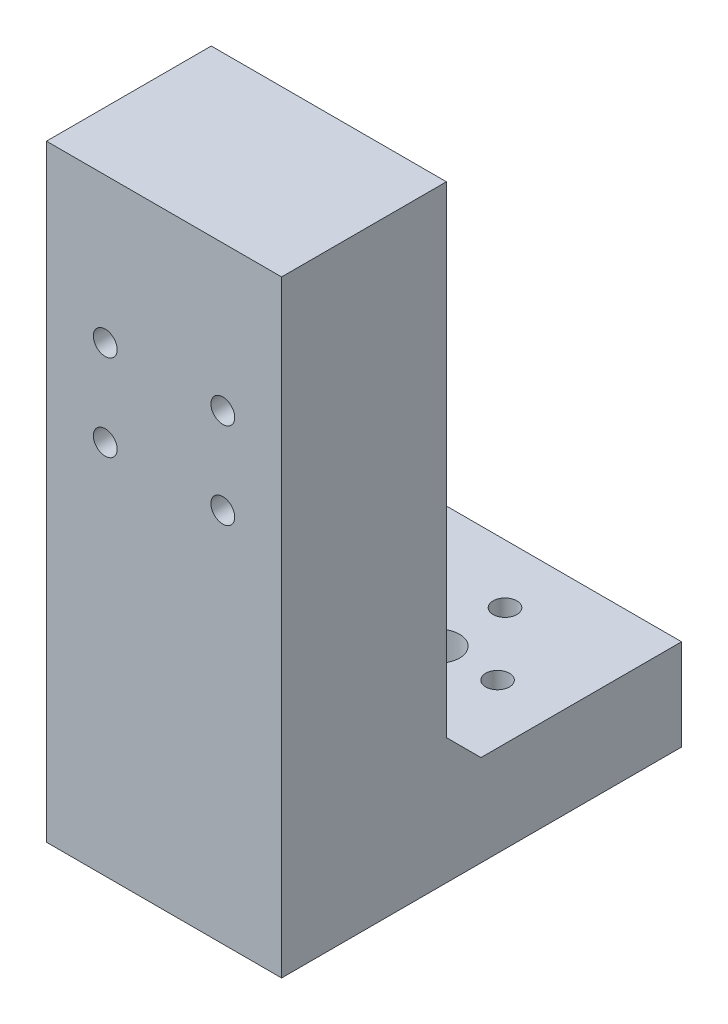
SolidWorks part; units mm, degrees
ref_plane "Front Plane" through (0, 0, 0) normal (0, 0, 1) x (1, 0, 0)
ref_plane "Top Plane" through (0, 0, 0) normal (0, 1, 0) x (1, 0, 0)
ref_plane "Right Plane" through (0, 0, 0) normal (1, 0, 0) x (0, 0, -1)
sketch "Sketch5" plane through (0, 0, 0) normal (0, 1, 0) x (1, 0, 0)
  line L1 (-2.6024, 18.1033) -> (31.3976, 18.1033)
  line L2 (-2.6024, 18.1033) -> (-2.6024, -15.8967)
  line L3 (-2.6024, -15.8967) -> (31.3976, -15.8967)
  line L4 (31.3976, 18.1033) -> (31.3976, -15.8967)
  dimension "D1" = 34
  dimension "D2" = 34
extrude "Boss-Extrude1" add sketch "Sketch5" along normal blind 13.19
sketch "Sketch6" plane through (0, 0, 15.8967) normal (0, 0, 1) x (1, 0, 0)
  line L1 (-2.6024, 0) -> (31.3976, 0)
  line L2 (-2.6024, 0) -> (-2.6024, 87.79)
  line L3 (-2.6024, 87.79) -> (31.3976, 87.79)
  line L4 (31.3976, 0) -> (31.3976, 87.79)
  dimension "D1" = 34
  dimension "D2" = 87.79
extrude "Boss-Extrude2" add sketch "Sketch6" along normal blind 23.83
sketch "Sketch7" plane through (0, 13.19, 0) normal (0, 1, 0) x (1, 0, 0)
  line L0 (31.3976, -15.8967) -> (31.3976, 18.1033) construction
  circle A0 centre (14.3976, 0) radius 3
  dimension "D2" = 6
  dimension "D1" = 17
extrude "Cut-Extrude1" cut sketch "Sketch7" against normal blind 21.83
sketch "Sketch8" plane through (0, 0, 39.7267) normal (0, 0, 1) x (1, 0, 0)
  line L0 (-2.6024, 87.79) -> (-2.6024, 0) construction
  line L1 (31.3976, 0) -> (31.3976, 87.79) construction
  circle A0 centre (5.8976, 66.7932) radius 1.72
  circle A1 centre (22.8976, 66.7932) radius 1.72
  circle A2 centre (5.8976, 54.3106) radius 1.72
  circle A3 centre (22.8976, 54.3106) radius 1.72
  dimension "D1" = 3.44
  dimension "D2" = 3.44
  dimension "D3" = 3.44
  dimension "D4" = 3.44
  dimension "D5" = 8.5
  dimension "D6" = 8.5
  dimension "D7" = 8.5
  dimension "D8" = 8.5
extrude "Cut-Extrude2" cut sketch "Sketch8" against normal blind 31.83
sketch "Sketch9" plane through (0, 13.19, 0) normal (0, 1, 0) x (1, 0, 0)
  line L0 (-2.6024, 18.1033) -> (-2.6024, -15.8967) construction
  line L1 (-2.6024, -15.8967) -> (31.3976, -15.8967) construction
  line L2 (31.3976, -15.8967) -> (31.3976, 18.1033) construction
  line L3 (31.3976, 18.1033) -> (-2.6024, 18.1033) construction
  circle A0 centre (22.8976, 0) radius 1.72
  circle A1 centre (14.3691, 9.6033) radius 1.72
  circle A2 centre (14.3691, -7.3967) radius 1.72
  circle A3 centre (5.8976, 0) radius 1.72
  dimension "D1" = 3.44
  dimension "D2" = 3.44
  dimension "D3" = 3.44
  dimension "D4" = 3.44
  dimension "D5" = 8.5
  dimension "D6" = 8.5
  dimension "D7" = 8.5
  dimension "D8" = 8.5
extrude "Cut-Extrude3" cut sketch "Sketch9" against normal blind 31.83
ref_plane "Plane2" through (-0.6024, 0, 0) normal (-1, 0, 0) x (0, 0, 1)
sketch "Sketch20" plane through (-0.6024, 0, 0) normal (-1, 0, 0) x (0, 0, 1)
  line L0 (10.8967, 13.19) -> (15.8967, 18.19)
  line L1 (-18.1033, 13.19) -> (15.8967, 13.19) construction
  line L2 (15.8967, 87.79) -> (15.8967, 13.19) construction
rib "Rib18" sketch "Sketch20" sketch "Sketch20" thickness 2 parameters "D1"=2
ref_plane "Plane3" through (29.3976, 0, 0) normal (1, 0, 0) x (0, 0, -1)
sketch "Sketch21" plane through (29.3976, 0, 0) normal (1, 0, 0) x (0, 0, -1)
  line L0 (-15.8967, 18.19) -> (-10.8967, 13.19)
rib "Rib19" sketch "Sketch21" sketch "Sketch21" thickness 2 parameters "D1"=2
equation "\"P\"= 300"
equation "\"SF\"= 3"
equation "\"d\" = 0.3mm"
equation "\"B\"= 34mm"
equation "\"E\" = 1600"
equation "\"L1\" = 18"
equation "\"Moment1\" = \"P\" * \"L1\""
equation "\"MOI\" = \"Moment1\" * ( \"B\" ^ 2 ) / ( 2 * \"E\" * \"d\" )"
equation "\"t1\"= ( ( \"MOI\" * 12 ) / \"B\" ) ^ ( 1 / 3 )"
equation "\"Motor\"= 74.6mm"
equation "\"Length2\"= \"t1\" + \"Motor\""
equation "\"Moment2\"= \"P\" * ( \"Length2\" + \"L1\" )"
equation "\"t2\"= ( ( 6 * \"Moment2\" * \"SF\" ) / ( \"B\" * \"Sy\" ) ) ^ ( 1 / 2 )"
equation "\"Sy\"= 29.6"
equation "\"Gearbox\" = 28"
equation "\"Shaft\"= 6mm"
